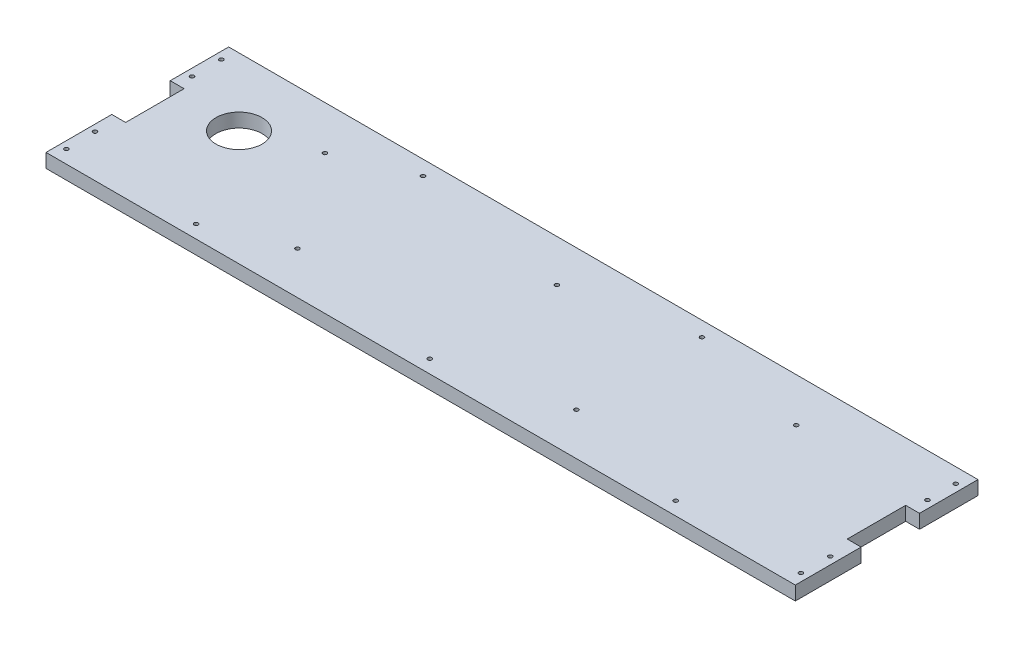
SolidWorks part; units mm, degrees
ref_plane "Front Plane" through (0, 0, 0) normal (0, 0, 1) x (1, 0, 0)
ref_plane "Top Plane" through (0, 0, 0) normal (0, 1, 0) x (1, 0, 0)
ref_plane "Right Plane" through (0, 0, 0) normal (1, 0, 0) x (0, 0, -1)
sketch "Sketch1" plane through (0, 0, 0) normal (0, 0, 1) x (1, 0, 0)
  line L1 (-840.4586, 543.2436) -> (-1865.9199, 543.2436)
  line L2 (-840.4586, 543.2436) -> (-840.4586, 562.2436)
  line L3 (-840.4586, 562.2436) -> (-1865.9199, 562.2436)
  line L4 (-1865.9199, 543.2436) -> (-1865.9199, 562.2436)
  line L5 (-1865.9199, 802.9784) -> (-1865.9199, 503.2436) construction
  line L6 (-840.4586, 503.2436) -> (-840.4586, 802.9784) construction
  dimension "D2" = 19
extrude "Boss-Extrude1" add sketch "Sketch1" along normal blind 250
sketch "Sketch2" plane through (0, 543.2436, 0) normal (0, -1, 0) x (1, 0, 0)
  circle A0 centre (-1759.4145, 92.3709) radius 31.4746 construction
  circle A1 centre (-1759.4145, 92.3709) radius 31.4746
extrude "Cut-Extrude1" cut sketch "Sketch2" against normal blind 19
sketch "Sketch3" plane through (-840.4586, 0, 0) normal (1, 0, 0) x (0, 0, -1)
  line L0 (-250, 543.2436) -> (0, 543.2436) construction
  line L1 (-160, 543.2436) -> (-80, 543.2436)
  line L2 (-160, 543.2436) -> (-160, 562.2436)
  line L3 (-160, 562.2436) -> (-80, 562.2436)
  line L4 (-80, 543.2436) -> (-80, 562.2436)
  line L5 (-250, 562.2436) -> (0, 562.2436) construction
  line L6 (0, 543.2436) -> (0, 562.2436) construction
  dimension "D1" = 80
extrude "Cut-Extrude2" cut sketch "Sketch3" against normal blind 19
sketch "Sketch4" plane through (-1865.9199, 0, 0) normal (-1, 0, 0) x (0, 0, 1)
  line L0 (250, 562.2436) -> (0, 562.2436) construction
  line L1 (160, 562.2436) -> (80, 562.2436)
  line L2 (160, 562.2436) -> (160, 543.2436)
  line L3 (160, 543.2436) -> (80, 543.2436)
  line L4 (80, 562.2436) -> (80, 543.2436)
  line L5 (250, 543.2436) -> (0, 543.2436) construction
extrude "Cut-Extrude3" cut sketch "Sketch4" against normal blind 19
sketch "Sketch5" plane through (0, 562.2436, 0) normal (0, 1, 0) x (1, 0, 0)
  line L0 (-840.4586, -24.1) -> (-840.4586, -16.5) construction
  line L1 (-840.4586, -250) -> (-840.4586, 0) construction
  line L2 (34.0801, -24.1) -> (-1865.9199, -24.1) construction
  line L3 (34.0801, -16.5) -> (-1865.9199, -16.5) construction
  line L4 (-850.7806, -24.1) -> (-850.7806, -16.5) construction
  line L5 (34.0801, -16.5) -> (-1865.9199, -16.5) construction
  line L6 (-850.7806, -20.3) -> (-1865.9199, -20) construction
  line L7 (-850.7806, -55.9) -> (-850.7806, -64.1) construction
  line L8 (-1865.9199, -24.1) -> (-1865.9199, -15.9) construction
  line L9 (34.0801, -55.9) -> (-1865.9199, -55.9) construction
  line L10 (34.0801, -64.1) -> (-1865.9199, -64.1) construction
  line L11 (-850.7806, -60) -> (-1865.9199, -60) construction
  line L16 (-850.7806, -187.9) -> (-850.7806, -196.1) construction
  line L17 (-850.7806, -196.1) -> (-850.7806, -192) construction
  line L18 (-850.7806, -192) -> (-1865.4737, -192) construction
  line L19 (-850.9051, -236.1) -> (-850.9051, -227.9) construction
  line L20 (-850.9051, -227.9) -> (-850.9051, -232) construction
  line L21 (-850.9051, -232) -> (-1866.591, -232) construction
  line L22 (34.0801, -196.1) -> (-1865.9199, -196.1) construction
  line L23 (34.0801, -187.9) -> (-1865.9199, -187.9) construction
  line L24 (34.0801, -227.9) -> (-1865.9199, -227.9) construction
  line L25 (34.0801, -236.1) -> (-1865.9199, -236.1) construction
  point P16 (-1579.8678, -20.0845)
  point P17 (-850.7806, -20.3)
  point P18 (-1197.9948, -20.1974)
  point P21 (-1865.9199, -20)
  point P23 (-1856.0313, -20.0029)
  point P31 (-1029.3638, -60)
  point P32 (-1359.1998, -57.55)
  point P33 (-1640.799, -60)
  point P34 (-1856.0313, -60)
  point P41 (-1197.9948, -192)
  point P46 (-1579.8678, -192)
  point P49 (-1856.0313, -192)
  point P52 (-1856.0313, -232)
  point P55 (-1678.4314, -232)
  point P56 (-850.7806, -192)
  point P57 (-1358.748, -232)
  point P58 (-1022.3175, -232)
  point P59 (0, 0)
  point P60 (0, 0)
  point P62 (0, 0)
  point P63 (0, 0)
  point P64 (0, 0)
  point P65 (0, 0)
  point P66 (0, 0)
hole_wizard "M5 Clearance Hole2" positions "3DSketch2" profile "Sketch7" hole size "M5" standard "ISO"
sketch3d "3DSketch2"
  line L1 (-850.7806, 562.2436, 55.9) -> (-850.7806, 562.2436, 64.1) construction
  line L2 (-850.7806, 562.2436, 60) -> (-1865.9199, 562.2436, 60) construction
  line L3 (-1197.9948, 562.2436, 192) -> (-854.5279, 562.2436, 192) construction
  point P3 (-850.7806, 562.2436, 20.3)
  point P6 (-1029.3638, 562.2436, 60)
  point P9 (-850.7806, 562.2436, 60)
  point P11 (-1197.9948, 562.2436, 20.1974)
  point P14 (-1359.1998, 562.2436, 57.55)
  point P17 (-1579.8678, 562.2436, 20.0845)
  point P23 (-1579.8678, 562.2436, 192)
  point P26 (-1197.9948, 562.2436, 192)
  point P29 (-1022.3175, 562.2436, 232)
  point P35 (-850.9051, 562.2436, 232)
  point P38 (-1358.748, 562.2436, 232)
  point P41 (-1579.8678, 562.2436, 192)
  point P43 (-1358.748, 562.2436, 232)
  point P49 (-1197.9948, 562.2436, 192)
  point P51 (-1359.1998, 562.2436, 57.55)
  point P55 (-1579.8678, 562.2436, 20.0845)
  point P57 (-1359.1998, 562.2436, 57.55)
  point P59 (-1197.9948, 562.2436, 20.1974)
  point P61 (-850.9051, 562.2436, 232)
  point P63 (-850.7806, 562.2436, 20.3)
  point P65 (-850.7806, 562.2436, 60)
  point P67 (-1865.9199, 539.5087, 9.5)
  point P73 (-1678.4314, 562.2436, 232)
  point P76 (-1865.9199, 539.5087, 221.5)
  point P79 (-1865.9199, 539.5087, 181.5)
  point P87 (-1865.9199, 539.5087, 221.5)
  point P89 (-1865.9199, 539.5087, 9.5)
  point P96 (-1856.0313, 562.2436, 232)
  point P99 (-1856.0313, 562.2436, 20.0029)
  point P110 (-850.7806, 562.2436, 60)
  point P114 (-1856.0313, 562.2436, 60)
  point P117 (-850.7806, 562.2436, 60)
  point P118 (-850.7806, 562.2436, 60)
  point P119 (-850.7806, 562.2436, 60)
  point P121 (-850.7806, 562.2436, 58.8568)
  point P128 (-1674.2251, 562.2436, 60)
  point P145 (-1856.9519, 562.2436, 191.9259)
  point P148 (-850.4361, 562.2436, 192.201)
sketch "Sketch7" plane through (-850.7806, 562.2436, 20.3) normal (1, 0, 0) x (0, 0, 1)
  line L0 (0, 0) -> (0, 20.6524)
  line L1 (0, 20.6524) -> (2.75, 19)
  line L2 (2.75, 19) -> (2.75, 0)
  line L5 (2.75, 0) -> (0, 0)
  line L10 (0, 20.6524) -> (-2.75, 19) construction
  line L11 (0, -6.35) -> (0, 107.95) construction
  point P3 (0, 0)
  dimension "Hole Dia." = 5.5
  dimension "Hole Depth" = 19
  dimension "Drill Angle" = 118
